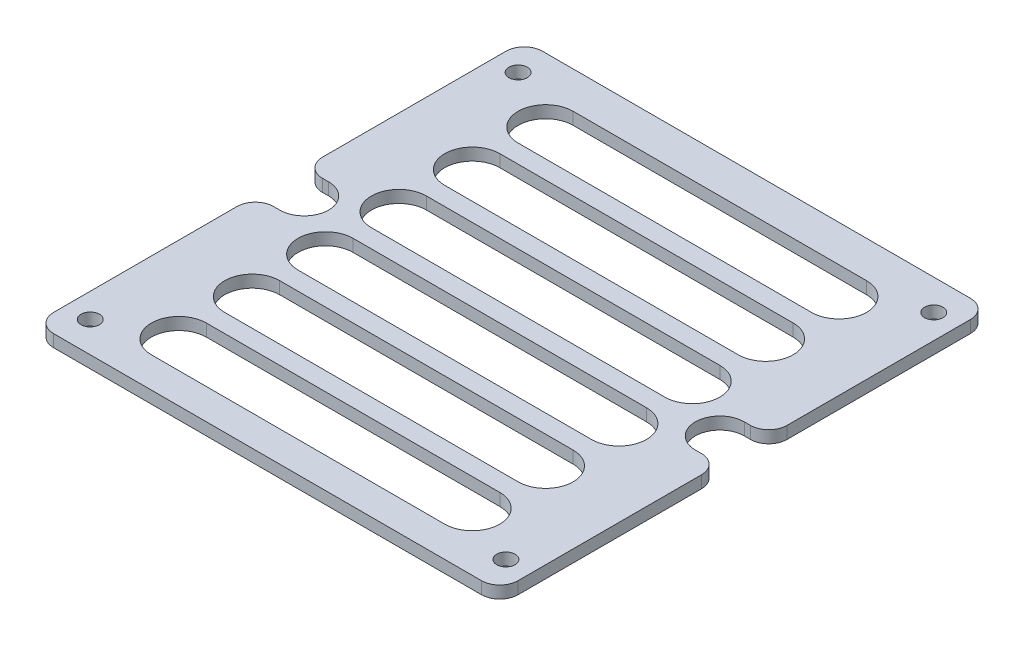
SolidWorks part; units mm, degrees
material "A-玻璃纤维"
ref_plane "前视基准面" through (0, 0, 0) normal (0, 0, 1) x (1, 0, 0)
ref_plane "上视基准面" through (0, 0, 0) normal (0, 1, 0) x (1, 0, 0)
ref_plane "右视基准面" through (0, 0, 0) normal (1, 0, 0) x (0, 0, -1)
sketch "草图1" plane through (0, 0, 0) normal (0, 1, 0) x (1, 0, 0)
  line L0 (-38, -30) -> (-38, -40)
  line L1 (-38, 40) -> (38, 40)
  line L2 (-38, 40) -> (-38, 30)
  line L3 (-38, -40) -> (38, -40)
  line L4 (38, 40) -> (38, 30)
  line L5 (0, -40) -> (0, 40) construction
  line L6 (-35, 0) -> (35, 0) construction
  line L7 (-38, 30) -> (-30, 30)
  line L8 (38, -30) -> (30, -30)
  line L9 (-38, -30) -> (-30, -30)
  line L10 (-30, 30) -> (-30, -30)
  line L11 (30, 30) -> (30, -30)
  line L12 (38, 30) -> (30, 30)
  line L13 (38, -30) -> (38, -40)
  point P0 (0, 0)
  dimension "D1" = 76
  dimension "D2" = 80
  dimension "D3" = 8
  dimension "D4" = 10
  dimension "D5" = 10
  dimension "D6" = 40
extrude "凸台-拉伸1" add sketch "草图1" along normal blind 2
sketch "草图2" plane through (0, 2, 0) normal (0, 1, 0) x (1, 0, 0)
  line L0 (-38, 40) -> (-38, 30) construction
  line L2 (38, 40) -> (-38, 40) construction
  circle A0 centre (-34, 35) radius 1.5
  dimension "D1" = 4
  dimension "D3" = 3
  dimension "D2" = 5
extrude "切除-拉伸1" cut sketch "草图2" against normal through all
mirror "镜向1" about plane through (0, 0, 0) normal (1, 0, 0) of "切除-拉伸1"
mirror "镜向2" about plane through (0, 0, 0) normal (0, 0, 1) of "镜向1", "切除-拉伸1"
sketch "草图3" plane through (0, 2, 0) normal (0, 1, 0) x (1, 0, 0)
  line L0 (-24, 29.5) -> (24, 29.5) construction
  line L1 (-24, 34) -> (24, 34)
  line L2 (-24, 25) -> (24, 25)
  line L3 (38, 40) -> (-38, 40) construction
  arc A0 (-24, 34) -> (-24, 25) centre (-24, 29.5) ccw
  arc A1 (24, 25) -> (24, 34) centre (24, 29.5) ccw
  point P2 (0, 29.5)
  dimension "D1" = 9
  dimension "D2" = 48
  dimension "D3" = 6
extrude "切除-拉伸2" cut sketch "草图3" against normal through all
pattern_linear "阵列(线性)1" count 6 spacing 12 along (0, 0, 1) of "切除-拉伸2"
sketch "草图4" plane through (30, 0, 0) normal (1, 0, 0) x (0, 0, -1)
  line L1 (-30, 2) -> (30, 2)
  line L2 (-30, 2) -> (-30, 0)
  line L3 (-30, 0) -> (30, 0)
  line L4 (30, 2) -> (30, 0)
extrude "凸台-拉伸2" add sketch "草图4" along normal blind 8
mirror "镜向3" about plane through (0, 0, 0) normal (1, 0, 0) of "凸台-拉伸2"
sketch "草图5" plane through (0, 2, 0) normal (0, 1, 0) x (1, 0, 0)
  line L0 (0, 7.7701) -> (0, -11) construction
  line L1 (-24, -11) -> (24, -11) construction
  circle A0 centre (34, 0) radius 1.55
  circle A1 centre (-34, 0) radius 1.55
  circle A3 centre (-34, -35) radius 1.5 construction
  dimension "D1" = 3.1
  dimension "D2" = 68
  dimension "D3" = 35
sketch "草图6" plane through (0, 2, 0) normal (0, 1, 0) x (1, 0, 0)
  line L0 (-38, 4) -> (-34, 4)
  line L1 (-38, 40) -> (-38, -40) construction
  line L2 (-34, -4) -> (-38, -4)
  line L3 (-38, -4) -> (-38, 4)
  line L4 (0, 44.6502) -> (0, -46.4483) construction
  line L5 (38, -4) -> (38, 4)
  line L6 (34, -4) -> (38, -4)
  line L7 (38, 4) -> (34, 4)
  arc A0 (-34, 4) -> (-34, -4) centre (-34, 0) cw
  circle A1 centre (-34, 0) radius 1.55 construction
  arc A2 (34, 4) -> (34, -4) centre (34, 0) ccw
  dimension "D1" = 4
extrude "切除-拉伸3" cut sketch "草图6" against normal through all
fillet "圆角1" radius 3 8 edges at (-38, 1, 4) (-38, 1, -4) (38, 1, -4) (38, 1, 4) (38, 1, 40) (-38, 1, 40) (-38, 1, -40) (38, 1, -40)
